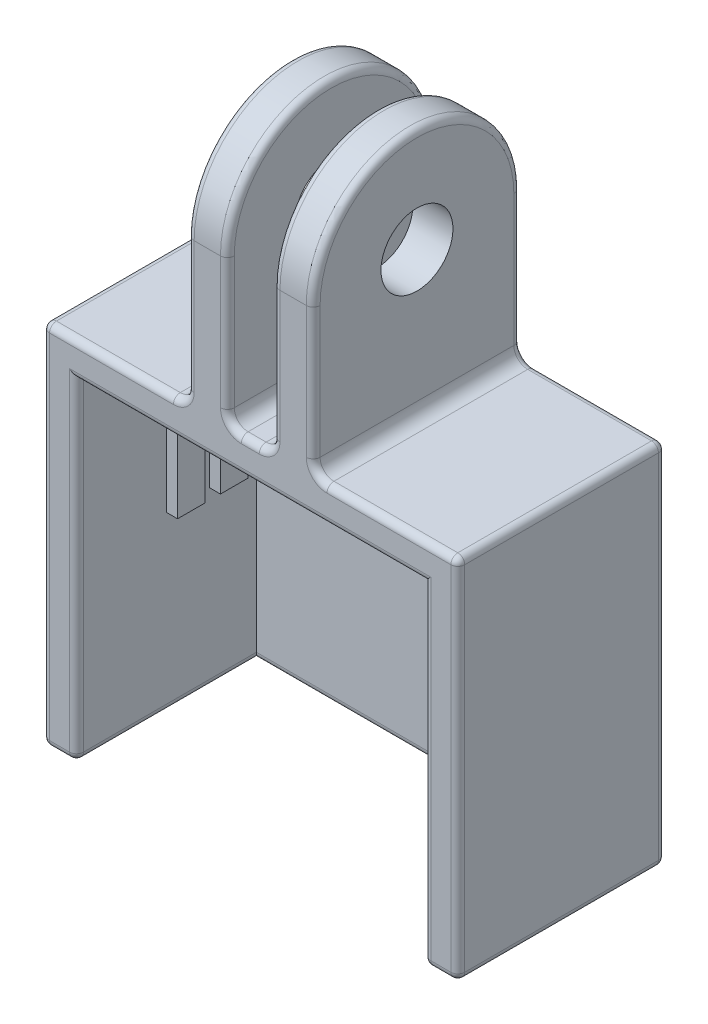
SolidWorks part; units mm, degrees
ref_plane "Front Plane" through (0, 0, 0) normal (0, 0, 1) x (1, 0, 0)
ref_plane "Top Plane" through (0, 0, 0) normal (0, 1, 0) x (1, 0, 0)
ref_plane "Right Plane" through (0, 0, 0) normal (1, 0, 0) x (0, 0, -1)
sketch "Sketch1" plane through (0, 0, 0) normal (0, 0, 1) x (1, 0, 0)
  line L1 (0.45, -18) -> (3.35, -18)
  line L2 (0.45, -18) -> (0.45, -36)
  line L3 (0.45, -36) -> (3.35, -36)
  line L4 (3.35, -18) -> (3.35, -36)
  line L6 (6.65, -18) -> (9.55, -18)
  line L7 (6.65, -18) -> (6.65, -36)
  line L8 (6.65, -36) -> (9.55, -36)
  line L9 (9.55, -18) -> (9.55, -36)
  line L10 (1.9, -18) -> (1.9, -15) construction
  line L11 (2.5, -15) -> (1.3, -15) construction
  line L12 (6.5, -16.4645) -> (9.7, -16.4645) construction
  line L13 (6.5, -25.5) -> (6.5, -15) construction
  line L14 (9.7, -25.5) -> (9.7, -16) construction
  line L15 (8.1, -16.4645) -> (8.1, -18) construction
  line L16 (1.9, -18) -> (1.9, -33) construction
  line L17 (11.1, -22.9) -> (11.1, -28.1) construction
  line L18 (12.5, -22.9) -> (9.7, -22.9) construction
  line L19 (9.7, -28.1) -> (12.5, -28.1) construction
  line L20 (11.1, -25.5) -> (1.9, -25.5) construction
  dimension "D1" = 2.9
  dimension "D2" = 18
  dimension "D3" = 15
extrude "Boss-Extrude1" add sketch "Sketch1" against normal blind 15
sketch "Sketch2" plane through (0.45, 0, 0) normal (-1, 0, 0) x (0, 0, 1)
  line L0 (-15, -18) -> (0, -18) construction
  line L1 (-15, -25.5) -> (-18.9278, -18.0447)
  line L2 (-18.9278, -18.0447) -> (-18.4156, -11.4468)
  line L3 (4.388, -18.0447) -> (0, -25.5)
  line L4 (-18.4156, -11.4468) -> (4.388, -9.7025)
  line L5 (4.388, -9.7025) -> (4.388, -18.0447)
  circle A0 centre (-7.5, -25.5) radius 2.6 construction
  circle A1 centre (-7.5, -25.5) radius 2.6
  circle A2 centre (-7.5, -25.5) radius 7.5
  line M2 (0, -36) -> (0, -18)
  line M3 (0, -18) -> (-15, -18)
  line M4 (-15, -18) -> (-15, -36)
extrude "Cut-Extrude2" cut sketch "Sketch2" against normal blind 15 contours L5 L4 L2 L1 L3 M4 M3 M2 | A2 M3 M4 | A2 M2 M3 | A1
sketch "Sketch3" plane through (0, -36, 0) normal (0, -1, 0) x (1, 0, 0)
  line L0 (3.35, -7.5) -> (6.65, -7.5) construction
  line L1 (-10, 0) -> (20, 0)
  line L2 (-10, 0) -> (-10, -15)
  line L3 (-10, -15) -> (20, -15)
  line L4 (20, 0) -> (20, -15)
  line L5 (3.35, -15) -> (3.35, 0) construction
  line L6 (6.65, -15) -> (6.65, 0) construction
  line L7 (5, -7.5) -> (5, -15) construction
  line L8 (0.45, 0) -> (3.35, 0) construction
  line L9 (0.45, -15) -> (3.35, -15) construction
  dimension "D1" = 30
extrude "Boss-Extrude2" add sketch "Sketch3" along normal blind 2.5
sketch "Sketch4" plane through (0, -38.5, 0) normal (0, -1, 0) x (1, 0, 0)
  line L0 (-10, -15) -> (20, -15) construction
  line L1 (-10, 0) -> (-7.55, 0)
  line L2 (-10, 0) -> (-10, -15)
  line L3 (-10, -15) -> (-7.55, -15)
  line L4 (-7.55, 0) -> (-7.55, -15)
  line L12 (20, 0) -> (17.55, 0)
  line L13 (20, 0) -> (20, -15)
  line L14 (20, -15) -> (17.55, -15)
  line L15 (17.55, 0) -> (17.55, -15)
  dimension "D1" = 25.1
extrude "Boss-Extrude3" add sketch "Sketch4" along normal blind 24
sketch "Sketch5" plane through (0, 0, -15) normal (0, 0, -1) x (-1, 0, 0)
  line L0 (-17.55, -62.5) -> (-17.55, -38.5) construction
  line L1 (7.55, -62.5) -> (-17.55, -62.5)
  line L2 (7.55, -62.5) -> (7.55, -40.5)
  line L3 (7.55, -40.5) -> (-17.55, -40.5)
  line L4 (-17.55, -62.5) -> (-17.55, -40.5)
  line L5 (7.55, -38.5) -> (-17.55, -38.5) construction
  dimension "D1" = 2
extrude "Boss-Extrude4" add sketch "Sketch5" against normal blind 2
sketch "Sketch6" plane through (0, -38.5, 0) normal (0, -1, 0) x (1, 0, 0)
  line L0 (-7.55, -15) -> (-7.55, 0) construction
  line L1 (-7.55, -6.5) -> (-6.75, -6.5)
  line L2 (-7.55, -6.5) -> (-7.55, -8.5)
  line L3 (-7.55, -8.5) -> (-6.75, -8.5)
  line L4 (-6.75, -6.5) -> (-6.75, -8.5)
  line L5 (17.55, 0) -> (17.55, -15) construction
  line L6 (-7.55, -9.6) -> (-6.75, -9.6)
  line L7 (-7.55, -9.6) -> (-7.55, -11.6)
  line L8 (-7.55, -11.6) -> (-6.75, -11.6)
  line L9 (-6.75, -9.6) -> (-6.75, -11.6)
  line L10 (17.55, -6.5) -> (16.75, -6.5)
  line L11 (17.55, -6.5) -> (17.55, -8.5)
  line L12 (17.55, -8.5) -> (16.75, -8.5)
  line L13 (16.75, -6.5) -> (16.75, -8.5)
  line L14 (-7.55, -13) -> (-7.55, 0) construction
  line L15 (17.55, -9.6) -> (16.75, -9.6)
  line L16 (17.55, -9.6) -> (17.55, -11.6)
  line L17 (17.55, -11.6) -> (16.75, -11.6)
  line L18 (16.75, -9.6) -> (16.75, -11.6)
  line L20 (17.55, -13) -> (-7.55, -13) construction
  dimension "D1" = 0.8
  dimension "D2" = 1.1
  dimension "D3" = 4.5
  dimension "D4" = 2
extrude "Boss-Extrude5" add sketch "Sketch6" along normal blind 11.5
fillet "Fillet1" radius 1 4 edges at (0.45, -36, -7.5) (6.65, -36, -7.5) (3.35, -36, -7.5) (9.55, -36, -7.5)
fillet "Fillet2" radius 0.5 46 edges at (6.3571, -35.7071, -15) (6.3571, -35.7071, 0) (6.65, -30.25, -15) (6.65, -30.25, 0) (6.65, -18, -7.5) (5, -36, -15) (3.6429, -35.7071, -15) (3.6429, -35.7071, 0) (3.35, -30.25, 0) (3.35, -30.25, -15) (3.35, -18, -7.5) (15.275, -36, 0) (9.8429, -35.7071, -15) (9.8429, -35.7071, 0) (9.55, -30.25, 0) (9.55, -30.25, -15) (9.55, -18, -7.5) (-5.275, -36, 0) (0.1571, -35.7071, -15) (0.1571, -35.7071, 0) (0.45, -30.25, -15) (0.45, -30.25, 0) (0.45, -18, -7.5) (5, -36, 0) (-7.55, -50.5, 0) (5, -38.5, 0) (17.55, -50.5, 0) (-8.775, -62.5, 0) (-7.55, -62.5, -6.5) (5, -62.5, -13) (20, -62.5, -7.5) (17.55, -62.5, -6.5) (18.775, -62.5, 0) (20, -49.25, 0) (5, -62.5, -15) (-10, -62.5, -7.5) (-10, -49.25, 0) (15.275, -36, -15) (20, -36, -7.5) (-5.275, -36, -15) (-10, -36, -7.5) (20, -49.25, -15) (-10, -49.25, -15) (5, -40.5, -13) (5, -38.5, -15) (5, -40.5, -15)
